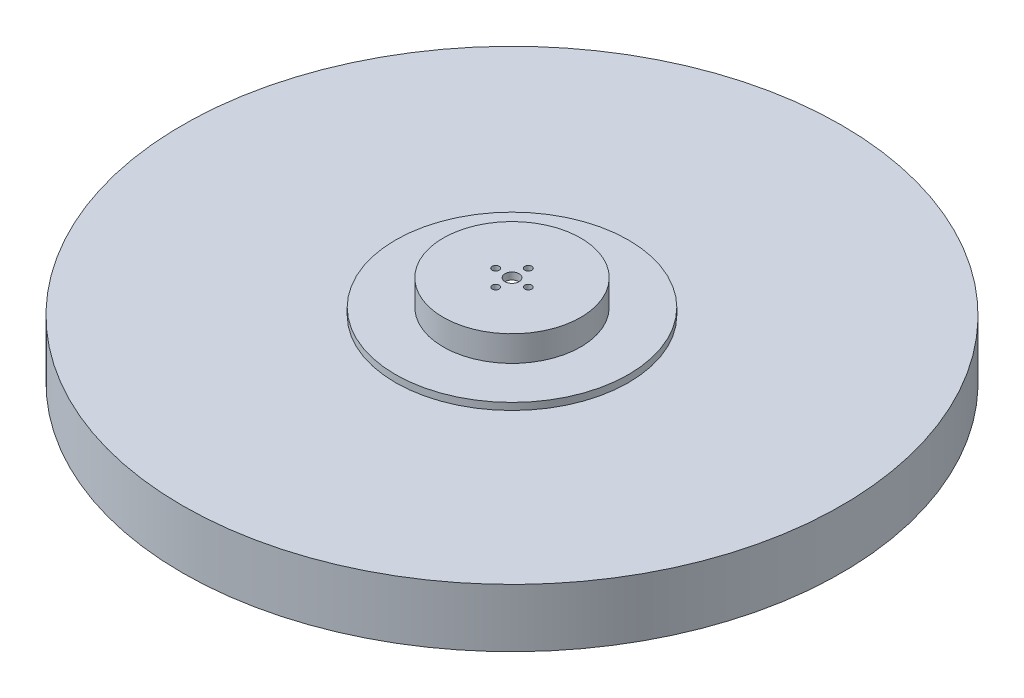
SolidWorks part; units mm, degrees
ref_plane "前视基准面" through (0, 0, 0) normal (0, 0, 1) x (1, 0, 0)
ref_plane "上视基准面" through (0, 0, 0) normal (0, 1, 0) x (1, 0, 0)
ref_plane "右视基准面" through (0, 0, 0) normal (1, 0, 0) x (0, 0, -1)
other "Configuration Table"
sketch "草图1" plane through (0, 0, 0) normal (0, 1, 0) x (1, 0, 0)
  circle A0 centre (0, 0) radius 141.4
  dimension "D1" = 282.8
extrude "凸台-拉伸1" add sketch "草图1" along normal blind 5
sketch "草图2" plane through (0, 5, 0) normal (0, 1, 0) x (1, 0, 0)
  circle A0 centre (0, 0) radius 50
extrude "凸台-拉伸2" add sketch "草图2" along normal blind 3
sketch "草图3" plane through (0, 8, 0) normal (0, 1, 0) x (1, 0, 0)
  circle A0 centre (0, 0) radius 29.5
  dimension "D1" = 59
extrude "凸台-拉伸3" add sketch "草图3" along normal blind 11
sketch "草图4" plane through (0, 0, 0) normal (0, -1, 0) x (1, 0, 0)
  circle A0 centre (0, 0) radius 27
  dimension "D1" = 54
extrude "切除-拉伸1" cut sketch "草图4" against normal blind 16
sketch "草图5" plane through (0, 16, 0) normal (0, -1, 0) x (1, 0, 0)
  line L0 (0, 0) -> (0, 7) construction
  circle A0 centre (0, 0) radius 3
  circle A1 centre (0, 7) radius 1.5
  circle A2 centre (7, 0) radius 1.5
  circle A3 centre (0, -7) radius 1.5
  circle A4 centre (-7, 0) radius 1.5
  point P14 (0, 0)
  dimension "D1" = 4
extrude "切除-拉伸2" cut sketch "草图5" against normal through all
sketch "草图6" plane through (0, 0, 0) normal (0, -1, 0) x (1, 0, 0)
  line L0 (0, 0) -> (0, 141.4) construction
  line L1 (0, 0) -> (122.456, 70.7) construction
  line L2 (0, 0) -> (122.456, -70.7) construction
  line L3 (0, 0) -> (0, -141.4) construction
  line L4 (0, 0) -> (-122.456, -70.7) construction
  line L5 (0, 0) -> (-122.456, 70.7) construction
  line L6 (-23.3827, 13.5) -> (-122.456, 70.7)
  line L7 (0, 27) -> (0, 141.4)
  circle A0 centre (0, 0) radius 141.4 construction
  circle A2 centre (0, 0) radius 27 construction
  arc A3 (-122.456, 70.7) -> (0, 141.4) centre (0, 0) cw
  point P13 (0, 0)
  dimension "D1" = 6
extrude "拉伸-薄壁1" add sketch "草图6" along normal blind 20 thin
pattern_circular "阵列(圆周)1" count 6 over 360 about axis through (0, 0, 0) along (0, 1, 0) of "拉伸-薄壁1"
